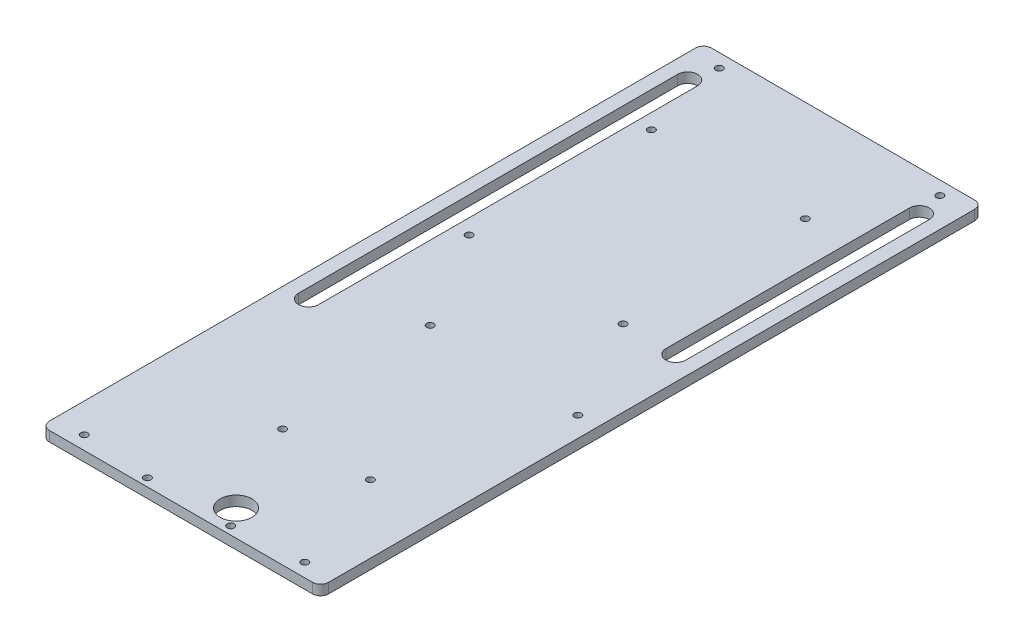
SolidWorks part; units mm, degrees
ref_plane "Front Plane" through (0, 0, 0) normal (0, 0, 1) x (1, 0, 0)
ref_plane "Top Plane" through (0, 0, 0) normal (0, 1, 0) x (1, 0, 0)
ref_plane "Right Plane" through (0, 0, 0) normal (1, 0, 0) x (0, 0, -1)
sketch "Sketch2" plane through (0, 0, 0) normal (0, 0, 1) x (1, 0, 0)
  line L0 (42.8242, -21.393) -> (42.8242, -24.5934)
  line L1 (0, -21.393) -> (0, -24.5934) construction
  line L2 (-46.0758, -24.5934) -> (42.8242, -24.5934)
  line L3 (-46.0758, -21.393) -> (-46.0758, -24.5934)
  line L4 (-46.0758, -21.393) -> (42.8242, -21.393)
  dimension "D1" = 88.9
  dimension "D2" = 3.2004
extrude "Boss-Extrude1" add sketch "Sketch2" along normal blind 210.82 contours L2 L0 L4 L3
sketch "Sketch3" plane through (0, -21.393, 0) normal (0, 1, 0) x (-1, 0, 0)
  line L0 (-42.8242, 208.28) -> (46.0758, 208.28) construction
  line L1 (38.5043, 9.421) -> (38.5043, 0) construction
  line L2 (46.0758, 0) -> (-42.8242, 0) construction
  line L3 (46.0758, 210.82) -> (-42.8242, 210.82) construction
  line L4 (36.73, 206.502) -> (46.0758, 206.502) construction
  line L5 (46.0758, 72.9493) -> (41.6793, 72.9493) construction
  line L6 (35.3293, 12.596) -> (41.6793, 12.596) construction
  line L7 (35.3293, 12.596) -> (35.3293, 133.3026)
  line L8 (35.3293, 133.3026) -> (41.6793, 133.3026) construction
  line L9 (41.6793, 12.596) -> (41.6793, 133.3026)
  line L10 (46.0758, 210.82) -> (-42.8242, 210.82) construction
  line L11 (-11.6838, 208.28) -> (-11.6838, 210.82) construction
  line L12 (-11.6838, 202.5188) -> (-11.6838, 208.28) construction
  line L13 (-7.6198, 202.5188) -> (-11.6838, 202.5188) construction
  line L14 (-42.8242, 210.82) -> (-42.8242, 0) construction
  line L15 (46.0758, 210.82) -> (46.0758, 0) construction
  line L16 (-33.4785, 206.502) -> (-33.4785, 210.82) construction
  line L17 (-33.4785, 206.502) -> (-42.8242, 206.502) construction
  line L18 (36.73, 206.502) -> (36.73, 210.82) construction
  line L19 (-33.4785, 4.318) -> (-42.8242, 4.318) construction
  line L20 (-33.4785, 4.318) -> (-33.4785, 0) construction
  line L21 (46.0758, 0) -> (-42.8242, 0) construction
  line L22 (36.73, 4.318) -> (36.73, 0) construction
  line L23 (36.73, 4.318) -> (46.0758, 4.318) construction
  line L24 (-18.451, 32.1211) -> (-18.451, 0) construction
  line L25 (-42.8242, 32.1211) -> (-18.451, 32.1211) construction
  line L26 (-18.451, 32.1211) -> (30.549, 32.1211) construction
  line L27 (-18.451, 32.1211) -> (-18.451, 90.1211) construction
  line L28 (30.549, 32.1211) -> (30.549, 90.1211) construction
  line L29 (-18.451, 90.1211) -> (30.549, 90.1211) construction
  line L30 (-42.8242, 122.5046) -> (-36.4214, 122.5046) construction
  line L31 (-36.4214, 122.5046) -> (-36.4214, 0) construction
  line L33 (-21.1814, 173.3046) -> (6.7586, 173.3046) construction
  line L34 (60.367, -163.7177) -> (66.7698, -163.7177) construction
  line L35 (66.7698, -163.7177) -> (96.7645, -163.7177) construction
  line L36 (-36.4214, 121.2346) -> (11.8386, 121.2346) construction
  line L37 (81.5791, -113.2668) -> (108.3182, -113.2668) construction
  line L38 (81.5791, -113.2668) -> (66.7698, -163.7177) construction
  line L39 (76.3923, -158.9273) -> (82.7952, -158.9273) construction
  line L40 (82.7952, -158.9273) -> (112.7898, -158.9273) construction
  line L41 (97.6044, -108.4763) -> (124.3436, -108.4763) construction
  line L42 (97.6044, -108.4763) -> (82.7952, -158.9273) construction
  line L43 (-36.4214, 121.2346) -> (-36.4214, 173.3046) construction
  line L44 (-36.4214, 173.3046) -> (11.8386, 173.3046) construction
  line L45 (11.8386, 121.2346) -> (11.8386, 173.3046) construction
  line L46 (-32.0777, 12.596) -> (-38.4277, 12.596) construction
  line L47 (-32.0777, 12.596) -> (-32.0777, 90.1226)
  line L48 (-32.0777, 90.1226) -> (-38.4277, 90.1226) construction
  line L49 (-38.4277, 12.596) -> (-38.4277, 90.1226)
  circle A0 centre (14.8338, 208.28) radius 1.1303
  arc A1 (35.3293, 133.3026) -> (41.6793, 133.3026) centre (38.5043, 133.3026) cw
  arc A2 (41.6793, 12.596) -> (35.3293, 12.596) centre (38.5043, 12.596) cw
  circle A3 centre (-11.6838, 208.28) radius 1.1303
  circle A4 centre (-7.6198, 202.5188) radius 5.08
  circle A5 centre (-33.4785, 206.502) radius 1.1303
  circle A6 centre (36.73, 206.502) radius 1.1303
  circle A7 centre (-33.4785, 4.318) radius 1.1303
  circle A8 centre (36.73, 4.318) radius 1.1303
  circle A9 centre (-18.451, 32.1211) radius 1.1303
  circle A10 centre (-18.451, 90.1211) radius 1.1303
  circle A11 centre (30.549, 90.1211) radius 1.1303
  circle A12 centre (30.549, 32.1211) radius 1.1303
  circle A13 centre (-21.1814, 173.3046) radius 1.1303
  circle A14 centre (-36.4214, 122.5046) radius 1.1303
  circle A15 centre (6.7586, 173.3046) radius 1.1303
  circle A16 centre (11.8386, 121.2346) radius 1.1303
  circle A17 centre (81.5791, -113.2668) radius 1.1303
  circle A18 centre (66.7698, -163.7177) radius 1.1303
  circle A19 centre (108.3182, -113.2668) radius 1.1303
  circle A20 centre (97.6044, -108.4763) radius 1.1303
  circle A21 centre (82.7952, -158.9273) radius 1.1303
  circle A22 centre (124.3436, -108.4763) radius 1.1303
  circle A23 centre (112.7898, -158.9273) radius 1.1303
  arc A24 (-32.0777, 12.596) -> (-38.4277, 12.596) centre (-35.2527, 12.596) cw
  arc A25 (-38.4277, 90.1226) -> (-32.0777, 90.1226) centre (-35.2527, 90.1226) cw
  point P12 (1.6258, 208.28)
  dimension "D5" = 2.2606
  dimension "D9" = 10.16
  dimension "D13" = 2.2606
  dimension "D15" = 9.3458
  dimension "D2" = 4.3965
  dimension "D3" = 120.7066
  dimension "D4" = 6.35
  dimension "D6" = 2.54
  dimension "D7" = 26.5176
  dimension "D8" = 13.208
  dimension "D10" = 5.7612
  dimension "D11" = 4.064
  dimension "D12" = 9.421
  dimension "D14" = 4.318
  dimension "D16" = 24.3732
  dimension "D17" = 32.1211
  dimension "D18" = 49
  dimension "D19" = 58
  dimension "D20" = 6.4028
  dimension "D21" = 122.5046
  dimension "D22" = 52.07
  dimension "D23" = 1.27
  dimension "D24" = 27.94
  dimension "D25" = 15.24
  dimension "D26" = 6.4028
  dimension "D27" = 29.9946
  dimension "D28" = 26.7391
  dimension "D29" = 73.641
  dimension "D30" = 52.5796
  dimension "D31" = 6.4028
  dimension "D32" = 29.9946
  dimension "D33" = 26.7391
  dimension "D34" = 73.641
  dimension "D35" = 52.5796
  dimension "D36" = 48.26
  dimension "D37" = 77.5266
extrude "Cut-Extrude1" cut sketch "Sketch3" against normal through all
sketch "Sketch4" plane through (0, 0, 0) normal (0, 0, -1) x (-1, 0, 0)
  line L0 (1.6258, -21.393) -> (1.6258, -24.5934) construction
  line L1 (46.0758, -21.393) -> (-42.8242, -21.393) construction
  line L2 (46.0758, -24.5934) -> (-42.8242, -24.5934) construction
sketch "Sketch5" plane through (42.8242, 0, 0) normal (1, 0, 0) x (0, 0, -1)
  line L0 (-105.41, -21.393) -> (-105.41, -24.5934) construction
  line L1 (-210.82, -21.393) -> (0, -21.393) construction
  line L2 (-210.82, -24.5934) -> (0, -24.5934) construction
fillet "Fillet2" radius 2.54 4 edges at (42.8242, -22.9932, 210.82) (-46.0758, -22.9932, 210.82) (-46.0758, -22.9932, 0) (42.8242, -22.9932, 0)
